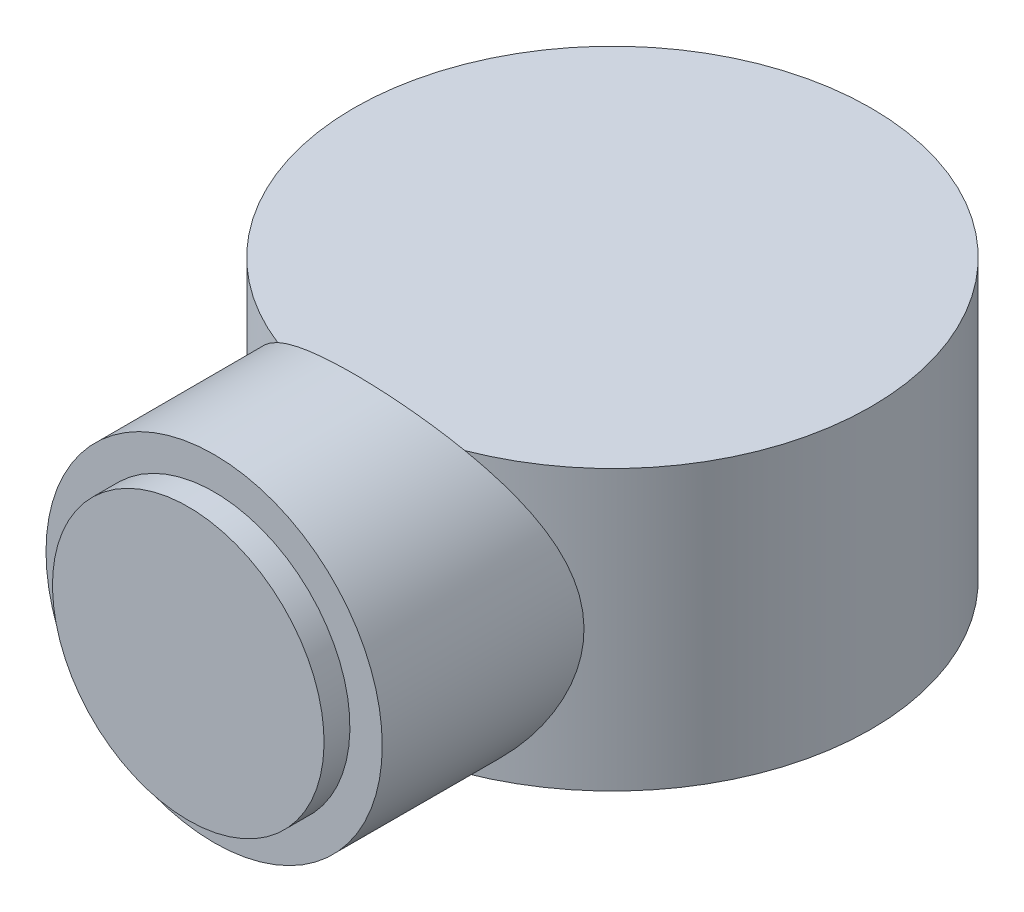
SolidWorks part; units mm, degrees
ref_plane "Front Plane" through (0, 0, 0) normal (0, 0, 1) x (1, 0, 0)
ref_plane "Top Plane" through (0, 0, 0) normal (0, 1, 0) x (1, 0, 0)
ref_plane "Right Plane" through (0, 0, 0) normal (1, 0, 0) x (0, 0, -1)
sketch "Sketch1" plane through (0, 0, 0) normal (0, 0, 1) x (1, 0, 0)
  circle A0 centre (0, 0) radius 50
  dimension "D1" = 100
extrude "Boss-Extrude1" add sketch "Sketch1" along normal mid plane 54
ref_plane "Plane1" through (77, 0, 0) normal (1, 0, 0) x (0, 0, -1)
sketch "Sketch2" plane through (77, 0, 0) normal (1, 0, 0) x (0, 0, -1)
  line L0 (-27, 50) -> (-27, -50) construction
  circle A0 centre (0, 0) radius 32.5
  dimension "D1" = 65
  dimension "D2" = 27
extrude "Boss-Extrude2" add sketch "Sketch2" against normal up to surface (27 mm away) up to face at (50, 0, 27)
sketch "Sketch3" plane through (77, 0, 0) normal (1, 0, 0) x (0, 0, -1)
  circle A0 centre (0, 0) radius 26.25
  dimension "D1" = 52.5
extrude "Boss-Extrude3" add sketch "Sketch3" along normal blind 5
sketch "Sketch4" plane through (82, 0, 0) normal (1, 0, 0) x (0, 0, -1)
  point P0 (0, 0)
move or copy body "Body-Move/Copy1" bodies to move or copy 103 copy no translate (-82, 0, 0) parameters "D1"=0, "D2"=0, "D3"=0
move or copy body "Body-Move/Copy2" bodies to move or copy 104 copy no rotation origin (0, 0, 0) rotation axis (-0.5774, -0.5774, -0.5774) rotation angle 120
sketch "Sketch5" plane through (0, 0, 0) normal (0, 1, 0) x (1, 0, 0)
  point P0 (0, 82)
